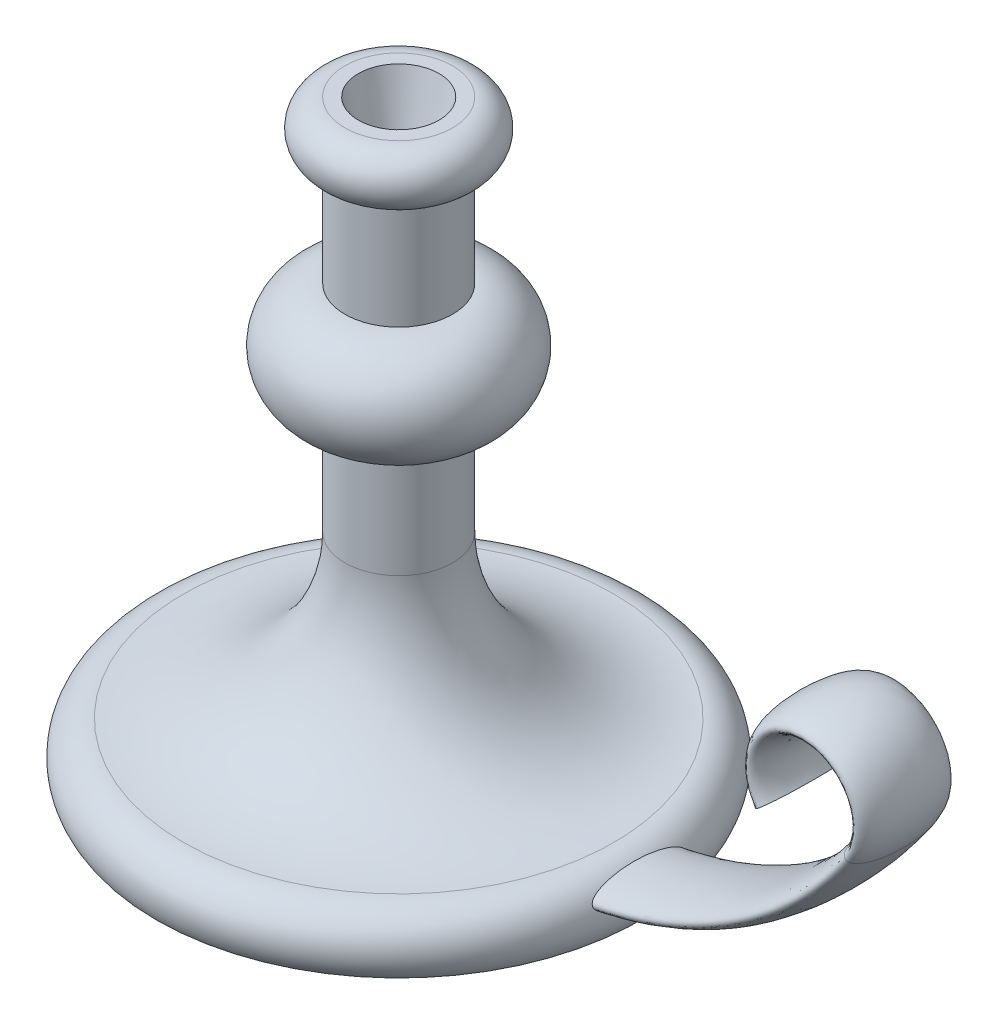
SolidWorks part; units mm, degrees
ref_plane "Спереди" through (0, 0, 0) normal (0, 0, 1) x (1, 0, 0)
ref_plane "Сверху" through (0, 0, 0) normal (0, 1, 0) x (1, 0, 0)
ref_plane "Справа" through (0, 0, 0) normal (1, 0, 0) x (0, 0, -1)
sketch "Эскиз1" plane through (0, 0, 0) normal (0, 0, 1) x (1, 0, 0)
  line L0 (0, 0) -> (0, 220)
  line L1 (0, 220) -> (20, 220)
  line L2 (0, 0) -> (90, 0)
  line L3 (20, 200) -> (20, 160)
  line L4 (20, 120) -> (20, 80)
  arc A0 (20, 220) -> (20, 200) centre (20, 210) cw
  arc A1 (20, 160) -> (20, 120) centre (20, 140) cw
  arc A2 (20, 80) -> (80, 20) centre (80, 80) ccw
  arc A3 (80, 20) -> (90, 0) centre (80, 7.5) cw
  dimension "D4" = 10
  dimension "D5" = 20
  dimension "D6" = 40
  dimension "D8" = 12.5
  dimension "D9" = 60
  dimension "D1" = 220
  dimension "D2" = 20
  dimension "D3" = 90
  dimension "D7" = 80
revolve "Повернуть1" add sketch "Эскиз1" angle 360 about L0
sketch "Эскиз2" plane through (0, 0, 0) normal (0, 0, 1) x (1, 0, 0)
  line L0 (0, 10) -> (60, 10)
  line L2 (0, 227.4356) -> (0, 175.1288) construction
  line L3 (0, 200) -> (0, 160) construction
  arc A0 (60, 10) -> (183.5921, 75) centre (60, 160) ccw
  arc A1 (183.5921, 75) -> (150.6342, 75) centre (167.1131, 86.3333) ccw
  point P8 (0, 0)
  point P9 (0, 0)
  point P10 (0, 0)
  point P13 (0, 0)
  dimension "D3" = 150
  dimension "D4" = 20
  dimension "D1" = 60
  dimension "D2" = 65
  dimension "D5" = 10
sketch "Эскиз3" plane through (0, 0, 0) normal (1, 0, 0) x (0, 0, -1)
  line L0 (0, 75) -> (0, 10) construction
  line L1 (0, 126.8188) -> (0, -13.6376) construction
  ellipse E0 centre (0, 10) end of major axis (17.5, 10) minor radius 5
  point P1 (0, 0)
  dimension "D1" = 10
  dimension "D2" = 35
sweep "По траектории1" add profiles "Эскиз3" path "Эскиз2"
sketch "Эскиз4" plane through (0, 220, 0) normal (0, 1, 0) x (1, 0, 0)
  circle A0 centre (0, 0) radius 15
  dimension "D1" = 30
extrude "Вырез-Вытянуть1" cut sketch "Эскиз4" against normal blind 25 draft 15
